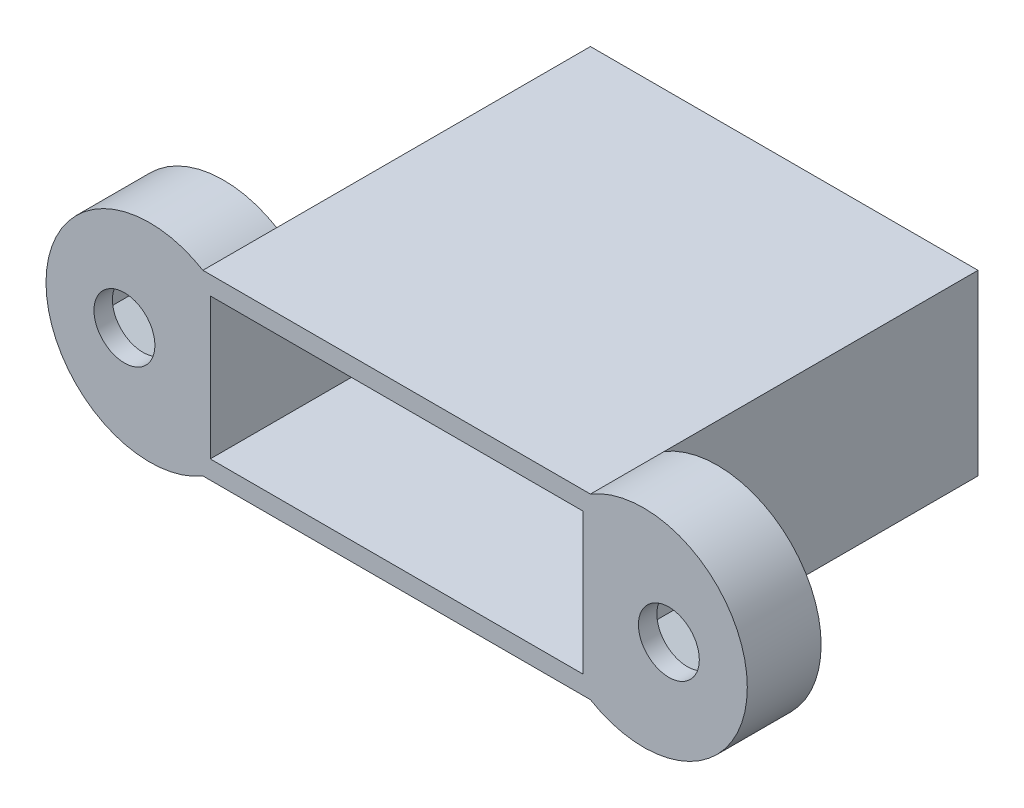
SolidWorks part; units mm, degrees
ref_plane "Front Plane" through (0, 0, 0) normal (0, 0, 1) x (1, 0, 0)
ref_plane "Top Plane" through (0, 0, 0) normal (0, 1, 0) x (1, 0, 0)
ref_plane "Right Plane" through (0, 0, 0) normal (1, 0, 0) x (0, 0, -1)
sketch "Sketch1" plane through (0, 0, 0) normal (0, 0, 1) x (1, 0, 0)
  line L5 (-10.0784, 4.9265) -> (10.9216, 4.9265)
  line L6 (-10.0784, 4.9265) -> (-10.0784, -4.7235)
  line L7 (-10.0784, -4.7235) -> (10.9216, -4.7235)
  line L8 (10.9216, 4.9265) -> (10.9216, -4.7235)
  point P4 (0.4216, 0.1015)
  dimension "D1" = 9.65
  dimension "D2" = 21
extrude "Boss-Extrude1" add sketch "Sketch1" along normal blind 21
sketch "Sketch3" plane through (0, 0, 21) normal (0, 0, 1) x (1, 0, 0)
  line L0 (-10.0784, 4.9265) -> (-10.0784, -4.7235) construction
  line L5 (-9.6784, 3.9265) -> (10.5216, 3.9265)
  line L6 (-9.6784, 3.9265) -> (-9.6784, -3.7235)
  line L7 (-9.6784, -3.7235) -> (10.5216, -3.7235)
  line L8 (10.5216, 3.9265) -> (10.5216, -3.7235)
  line L9 (-9.6784, 3.9265) -> (10.5216, -3.7235) construction
  line L10 (-9.6784, -3.7235) -> (10.5216, 3.9265) construction
  line L11 (-10.0784, -4.7235) -> (10.9216, -4.7235) construction
  point P4 (0.4216, 0.1015)
  dimension "D1" = 20.2
  dimension "D2" = 7.65
  dimension "D3" = 0.4
  dimension "D4" = 1
extrude "Cut-Extrude1" cut sketch "Sketch3" against normal blind 19.6
sketch "Sketch5" plane through (0, 0, 1.4) normal (0, 0, 1) x (1, 0, 0)
  line L0 (10.5216, 3.9265) -> (-9.6784, 3.9265) construction
  line L1 (-0.8284, 1.9265) -> (1.6716, 1.9265) construction
  line L4 (-0.8284, 3.9265) -> (1.6716, 3.9265)
  line L5 (-0.8284, -0.0735) -> (1.6716, -0.0735)
  arc A0 (-0.8284, 3.9265) -> (-0.8284, -0.0735) centre (-0.8284, 1.9265) ccw
  arc A1 (1.6716, -0.0735) -> (1.6716, 3.9265) centre (1.6716, 1.9265) ccw
  point P3 (0.4216, 0.1297)
  point P9 (0.4216, 1.9265)
  dimension "D1" = 0
  dimension "D2" = 4
extrude "Cut-Extrude2" cut sketch "Sketch5" against normal blind 19.6
sketch "Sketch20" plane through (0, 0, 21) normal (0, 0, 1) x (1, 0, 0)
  line L0 (-18.5784, 0.1015) -> (-10.0784, 0.1015) construction
  line L20 (-10.0784, 4.9265) -> (-10.0784, -4.7235) construction
  line L21 (-10.0784, 4.9265) -> (-10.0784, -4.7235)
  arc A0 (-10.0784, 4.9265) -> (-10.0784, -4.7235) centre (-12.9589, 0.1015) ccw
  dimension "D1" = 8.5
extrude "Boss-Extrude2" add sketch "Sketch20" against normal blind 4
sketch "Sketch21" plane through (0, 0, 17) normal (0, 0, -1) x (-1, 0, 0)
  line L0 (18.5784, 0.1015) -> (10.0784, 0.1015) construction
  line L1 (10.0784, 4.9265) -> (10.0784, -4.7235) construction
  line L9 (14.3284, 3.8515) -> (11.0808, 1.9765)
  line L16 (11.0808, 1.9765) -> (11.0808, -1.7735)
  line L17 (11.0808, -1.7735) -> (14.3284, -3.6485)
  line L18 (14.3284, -3.6485) -> (17.576, -1.7735)
  line L19 (17.576, -1.7735) -> (17.576, 1.9765)
  line L20 (17.576, 1.9765) -> (14.3284, 3.8515)
  arc A0 (10.0784, -4.7235) -> (10.0784, 4.9265) centre (12.9589, 0.1015) ccw construction
  circle A1 centre (14.3284, 0.1015) radius 3.2476 construction
  point P8 (11.0808, 0.1015)
  dimension "D1" = 7.5
  dimension "D2" = 1.0024
extrude "Cut-Extrude3" cut sketch "Sketch21" against normal blind 3
sketch "Sketch22" plane through (0, 0, 20) normal (0, 0, -1) x (-1, 0, 0)
  line L0 (14.3284, 3.8515) -> (14.3284, -3.6485) construction
  circle A1 centre (14.3284, 0.1015) radius 1.65
  dimension "D1" = 3.3
extrude "Cut-Extrude4" cut sketch "Sketch22" against normal blind 3
sketch "Sketch23" plane through (0, 0, 21) normal (0, 0, 1) x (1, 0, 0)
  line L0 (10.9216, 4.9265) -> (10.9216, -4.7235)
  line L1 (10.9216, 0.1015) -> (19.4216, 0.1015) construction
  arc A0 (10.9216, 4.9265) -> (10.9216, -4.7235) centre (13.8022, 0.1015) cw
  dimension "D1" = 8.5
extrude "Boss-Extrude3" add sketch "Sketch23" against normal blind 4
sketch "Sketch24" plane through (0, 0, 17) normal (0, 0, -1) x (-1, 0, 0)
  line L0 (-19.4216, 0.1015) -> (-10.9216, 0.1015) construction
  line L1 (-10.9216, -4.7235) -> (-10.9216, 4.9265) construction
  line L3 (-15.1716, 3.8515) -> (-18.4192, 1.9765)
  line L4 (-18.4192, 1.9765) -> (-18.4192, -1.7735)
  line L5 (-18.4192, -1.7735) -> (-15.1716, -3.6485)
  line L6 (-15.1716, -3.6485) -> (-11.924, -1.7735)
  line L7 (-11.924, -1.7735) -> (-11.924, 1.9765)
  line L8 (-11.924, 1.9765) -> (-15.1716, 3.8515)
  arc A0 (-10.9216, 4.9265) -> (-10.9216, -4.7235) centre (-13.8022, 0.1015) ccw construction
  circle A1 centre (-15.1716, 0.1015) radius 3.2476 construction
  point P8 (-11.924, 0.1015)
  dimension "D1" = 7.5
  dimension "D2" = 1.0024
extrude "Cut-Extrude5" cut sketch "Sketch24" against normal blind 3
sketch "Sketch25" plane through (0, 0, 20) normal (0, 0, -1) x (-1, 0, 0)
  line L0 (-15.1716, -3.6485) -> (-15.1716, 3.8515) construction
  line L1 (-11.924, 1.9765) -> (-15.1716, 3.8515) construction
  line L2 (-15.1716, 3.8515) -> (-18.4192, 1.9765) construction
  circle A0 centre (-15.1716, 0.1015) radius 1.65
  dimension "D1" = 3.3
extrude "Cut-Extrude6" cut sketch "Sketch25" against normal blind 3
